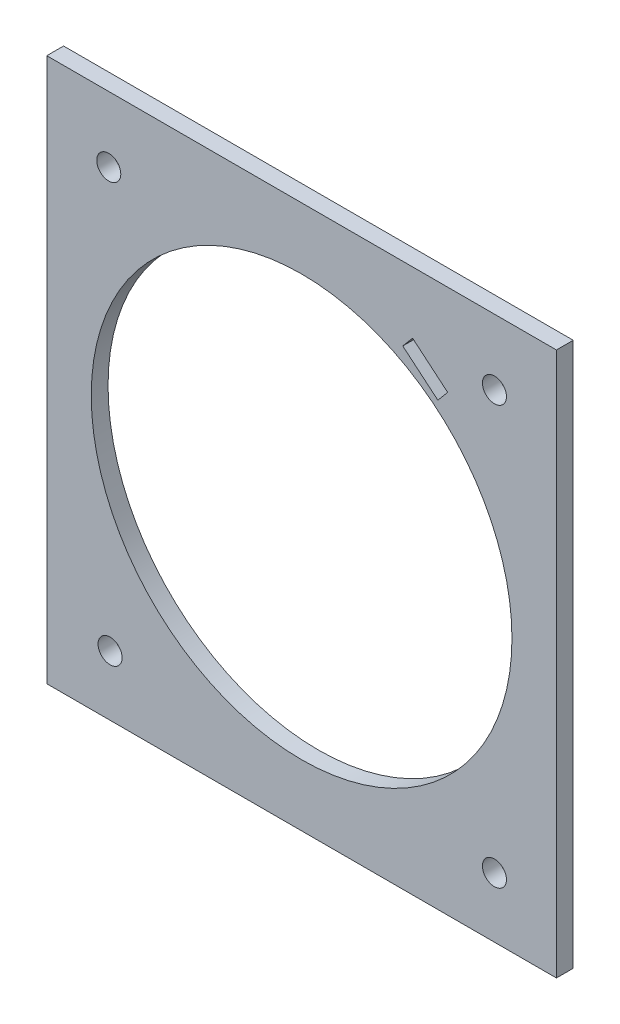
SolidWorks part; units mm, degrees
material "Acrylic (Medium-high impact)"
ref_plane "Front Plane" through (0, 0, 0) normal (0, 0, 1) x (1, 0, 0)
ref_plane "Top Plane" through (0, 0, 0) normal (0, 1, 0) x (1, 0, 0)
ref_plane "Right Plane" through (0, 0, 0) normal (1, 0, 0) x (0, 0, -1)
sketch "Sketch1" plane through (0, 0, 0) normal (0, 0, 1) x (1, 0, 0)
  line L1 (0, 0) -> (84.8, 0)
  line L2 (0, 0) -> (0, -90.5)
  line L3 (0, -90.5) -> (84.8, -90.5)
  line L4 (84.8, 0) -> (84.8, -90.5)
extrude "Boss-Extrude1" add sketch "Sketch1" along normal blind 2.794 contours L1 L4 L3 L2
sketch "Sketch2" plane through (0, 0, 2.794) normal (0, 0, 1) x (1, 0, 0)
  line L0 (42.4, 0) -> (42.4, -90.5) construction
  line L1 (0, 0) -> (84.8, 0) construction
  line L2 (0, 0) -> (0, -90.5) construction
  line L3 (0, -90.5) -> (84.8, -90.5) construction
  line L4 (84.8, 0) -> (84.8, -90.5) construction
  circle A0 centre (10.315, -10.905) radius 2
  circle A1 centre (74.485, -10.905) radius 2
  circle A2 centre (74.485, -80.5) radius 2
  circle A3 centre (10.533, -80.5) radius 2
  point P4 (10.315, -10.905)
  point P7 (74.485, -10.905)
  point P8 (74.485, -80.5)
  point P9 (10.533, -80.5)
  point P18 (10.533, -10.905)
  point P19 (10.533, -10.905)
  point P20 (10.533, -80.5)
  point P21 (10.533, -80.5)
  point P22 (0, 0)
  point P23 (74.485, -10.905)
  point P24 (74.485, -80.5)
  point P25 (74.485, -80.5)
  dimension "D3" = 4
  dimension "D4" = 4
  dimension "D5" = 4
extrude "Cut-Extrude1" cut sketch "Sketch2" against normal through all both and the other way through all
sketch "Sketch3" plane through (0, 0, 0) normal (0, 0, -1) x (-1, 0, 0)
  line L0 (-84.8, 0) -> (0, -90.5) construction
  line L1 (0, 0) -> (-84.8, -90.5) construction
  circle A0 centre (-42.4, -45.25) radius 1.7145
  dimension "D1" = 3.429
extrude "Cut-Extrude2" cut sketch "Sketch3" against normal through all both and the other way through all
sketch "Sketch4" plane through (0, 0, 0) normal (0, 0, -1) x (-1, 0, 0)
  line L4 (0, -90.5) -> (0, 0)
  line L5 (0, 0) -> (-84.8, 0)
  line L6 (-84.8, 0) -> (-84.8, -90.5)
  line L7 (-84.8, -90.5) -> (0, -90.5)
  line L8 (0, -90.5) -> (0, 0)
  line L9 (0, 0) -> (-84.8, 0)
  line L10 (-84.8, 0) -> (-84.8, -90.5)
  line L11 (-84.8, -90.5) -> (0, -90.5)
  circle A0 centre (-74.485, -80.5) radius 2 construction
  circle A1 centre (-10.533, -80.5) radius 2 construction
  circle A3 centre (-10.315, -10.905) radius 2 construction
  circle A4 centre (-74.485, -10.905) radius 2 construction
  circle A5 centre (-74.485, -80.5) radius 2
  circle A6 centre (-10.533, -80.5) radius 2
  circle A8 centre (-10.315, -10.905) radius 2
  circle A9 centre (-74.485, -10.905) radius 2
  circle A10 centre (-42.4, -45.25) radius 39.75
  circle A11 centre (-42.4, -45.25) radius 35
  dimension "D2" = 79.5
  dimension "D3" = 70
  dimension "D1" = 0
extrude "Cut-Extrude3" cut sketch "Sketch4" against normal blind 10 contours A11
sketch "Sketch5" plane through (0, 0, 2.794) normal (0, 0, 1) x (1, 0, 0)
  line L1 (60.8655, -10.2644) -> (66.7027, -15.1624)
  line L2 (60.8655, -10.2644) -> (59.2328, -12.2101)
  line L3 (59.2328, -12.2101) -> (65.0701, -17.1082)
  line L4 (66.7027, -15.1624) -> (65.0701, -17.1082)
  dimension "D1" = 2.54
  dimension "D2" = 7.62
extrude "Cut-Extrude4" cut sketch "Sketch5" against normal blind 10
